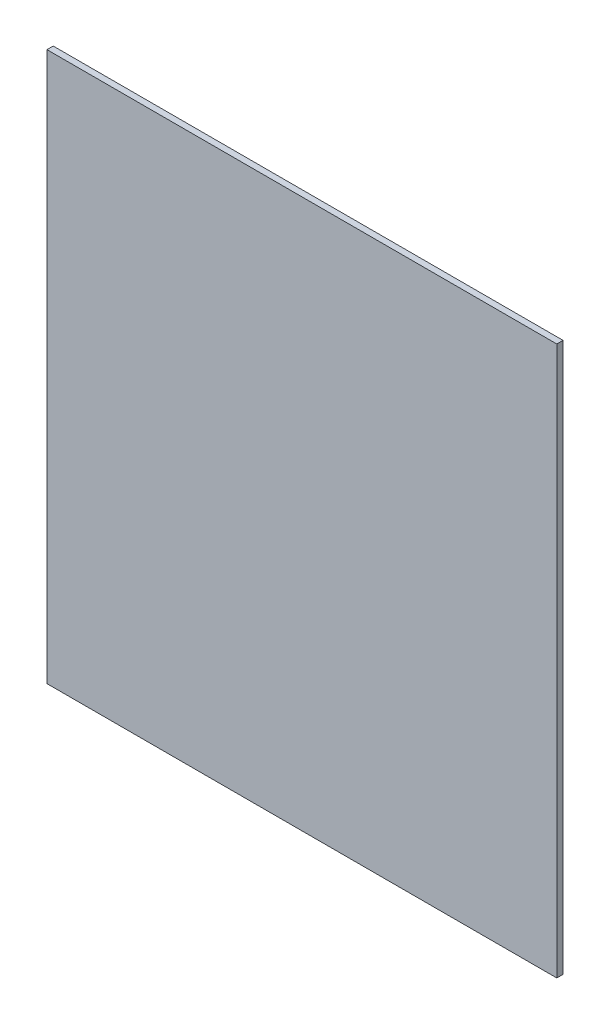
SolidWorks part; units mm, degrees
ref_plane "Front Plane" through (0, 0, 0) normal (0, 0, 1) x (1, 0, 0)
ref_plane "Top Plane" through (0, 0, 0) normal (0, 1, 0) x (1, 0, 0)
ref_plane "Right Plane" through (0, 0, 0) normal (1, 0, 0) x (0, 0, -1)
sketch "Sketch1" plane through (0, 0, 0) normal (0, 0, 1) x (1, 0, 0)
  line L1 (-53.2088, 16.5) -> (11.7912, 16.5)
  line L2 (-53.2088, 16.5) -> (-53.2088, -53.5)
  line L3 (-53.2088, -53.5) -> (11.7912, -53.5)
  line L4 (11.7912, 16.5) -> (11.7912, -53.5)
  dimension "D1" = 70
  dimension "D2" = 65
extrude "Boss-Extrude1" add sketch "Sketch1" along normal blind 0.8
